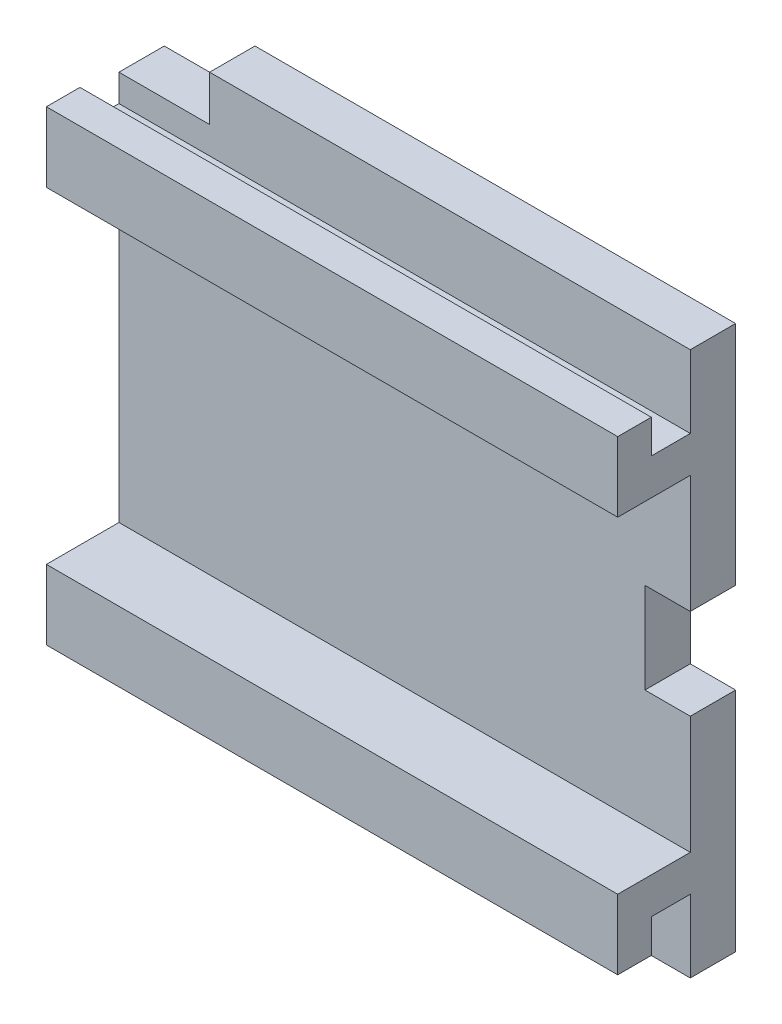
SolidWorks part; units mm, degrees
material "Alliage 1060"
ref_plane "Plan de dessus" through (0, 0, 0) normal (0, 0, 1) x (1, 0, 0)
ref_plane "Plan de droite" through (0, 0, 0) normal (0, 1, 0) x (1, 0, 0)
ref_plane "Plan de face" through (0, 0, 0) normal (1, 0, 0) x (0, 0, -1)
sketch "Esquisse1" plane through (0, 0, 0) normal (0, 0, 1) x (1, 0, 0)
  line L0 (63, 35) -> (58, 35)
  line L1 (0, 0) -> (10, 0)
  line L2 (0, 0) -> (0, 55)
  line L4 (63, 0) -> (63, 25)
  line L5 (58, 35) -> (58, 25)
  line L6 (58, 25) -> (63, 25)
  line L7 (63, 35) -> (63, 60)
  line L8 (53, 0) -> (63, 0)
  line L10 (53, 0) -> (53, 5)
  line L16 (10, 0) -> (10, 5)
  line L28 (10, 5) -> (53, 5)
  line L29 (10, 55) -> (0, 55)
  line L30 (10, 55) -> (10, 60)
  line L32 (10, 60) -> (63, 60)
  dimension "D1" = 63
  dimension "D2" = 5
  dimension "D3" = 5
  dimension "D4" = 10
  dimension "D5" = 5
  dimension "D6" = 25
  dimension "D9" = 10
  dimension "D10" = 10
extrude "Boss.-Extru.1" add sketch "Esquisse1" along normal blind 5
sketch "Esquisse5" plane through (0, 0, 0) normal (-1, 0, 0) x (0, 0, 1)
  line L0 (5, 55) -> (5, 0) construction
  line L1 (5, 55) -> (0, 55) construction
  line L2 (5, 60) -> (5, 55) construction
  line L3 (5, 0) -> (0, 0) construction
  circle A0 centre (2.5, 2.5) radius 1.5
  circle A1 centre (2.5, 57.5) radius 1.5
  dimension "D1" = 2.5
  dimension "D3" = 3
  dimension "D4" = 3
  dimension "D2" = 2.5
  dimension "D5" = 2.5
  dimension "D6" = 2.5
extrude "Enlèv. mat.-Extru.1" cut sketch "Esquisse5" against normal blind 15
sketch "Esquisse8" plane through (63, 0, 0) normal (1, 0, 0) x (0, 0, -1)
  line L0 (-5, 52) -> (-9.3, 52)
  line L1 (-5, 35) -> (-5, 60) construction
  line L2 (-9.3, 52) -> (-9.3, 55.7)
  line L3 (-9.3, 55.7) -> (-13, 55.7)
  line L4 (-13, 55.7) -> (-13, 48)
  line L5 (-13, 48) -> (-5, 48)
  line L6 (-5, 48) -> (-5, 52)
  line L7 (-5, 35) -> (-5, 25) construction
  line L8 (-5, 30) -> (-14.6026, 30) construction
  line L9 (-5, 60) -> (0, 60) construction
  line L10 (-5, 12) -> (-5, 8)
  line L11 (-13, 12) -> (-5, 12)
  line L12 (-13, 4.3) -> (-13, 12)
  line L13 (-9.3, 4.3) -> (-13, 4.3)
  line L14 (-9.3, 8) -> (-9.3, 4.3)
  line L15 (-5, 8) -> (-9.3, 8)
  dimension "D1" = 8
  dimension "D2" = 3.7
  dimension "D3" = 4
  dimension "D4" = 7.7
  dimension "D5" = 8
extrude "Boss.-Extru.2" add sketch "Esquisse8" against normal up to surface (63 mm away) up to face at (0, 2.5, 4)
